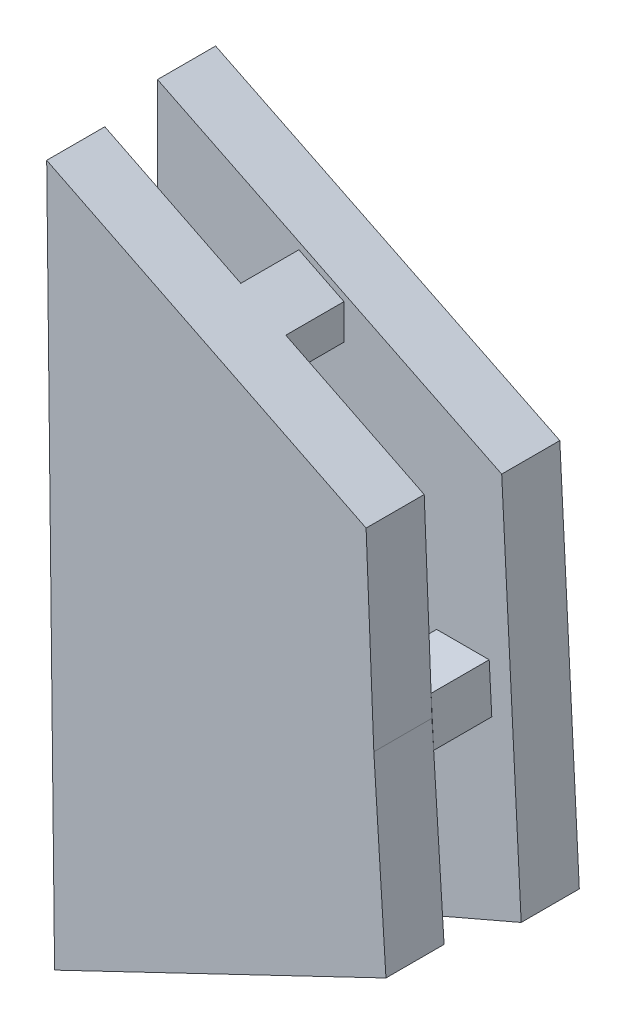
SolidWorks part; units mm, degrees
ref_plane "Front Plane" through (0, 0, 0) normal (0, 0, 1) x (1, 0, 0)
ref_plane "Top Plane" through (0, 0, 0) normal (0, 1, 0) x (1, 0, 0)
ref_plane "Right Plane" through (0, 0, 0) normal (1, 0, 0) x (0, 0, -1)
sketch "Sketch1" plane through (0, 0, 0) normal (0, 1, 0) x (1, 0, 0)
  line L0 (-4.6256, 12.4082) -> (9.4591, -14.08)
  line L1 (9.4591, -14.08) -> (-0.7045, -10.0781)
  line L2 (-0.7045, -10.0781) -> (-8.0443, 3.7254)
  line L3 (-8.0443, 3.7254) -> (-4.6256, 12.4082)
  dimension "D1" = 30
  dimension "D2" = 15.6337
sketch "Sketch20" plane through (0, 0, 0) normal (0, 0, 1) x (1, 0, 0)
  line L0 (-2.79, 109.4322) -> (-1.4345, -10.5678)
  line L2 (53.5013, 49.4322) -> (52.1695, 82.1069)
  line L3 (53.5013, 49.4322) -> (55.5864, 16.7673)
  line L4 (52.1695, 82.1069) -> (-2.79, 109.4322)
  line L5 (-1.4345, -10.5678) -> (55.5864, 16.7673)
  dimension "D1" = 120
extrude "Boss-Extrude1" add sketch "Sketch20" along normal blind 10
sketch "Sketch21" plane through (0, 0, 0) normal (0, 0, -1) x (-1, 0, 0)
  line L0 (2.1534, 53.0757) -> (-6.504, 53.0757)
  line L1 (2.79, 109.4322) -> (1.4345, -10.5678) construction
  line L2 (-6.504, 53.0757) -> (-6.504, 44.7938)
  line L3 (-6.504, 44.7938) -> (2.0599, 44.7938)
  line L4 (2.0599, 44.7938) -> (2.1534, 53.0757)
  line L5 (-53.3528, 53.0757) -> (-44.3058, 53.0757)
  line L6 (-53.5013, 49.4322) -> (-52.1695, 82.1069) construction
  line L7 (-44.3058, 53.0757) -> (-44.3058, 44.7938)
  line L8 (-44.3058, 44.7938) -> (-53.7974, 44.7938)
  line L9 (-55.5864, 16.7673) -> (-53.5013, 49.4322) construction
  line L10 (-53.7974, 44.7938) -> (-53.3528, 53.0757)
  line L11 (-20.6099, 0) -> (-20.6099, 9.1834)
  line L12 (1.4345, -10.5678) -> (-55.5864, 16.7673) construction
  line L13 (-20.6099, 9.1834) -> (-28.3581, 10.9397)
  line L14 (-28.3581, 10.9397) -> (-28.3581, 3.7144)
  line L15 (-28.3581, 3.7144) -> (-20.6099, 0)
  line L16 (-28.3581, 93.9457) -> (-28.3581, 87.9037)
  line L17 (-52.1695, 82.1069) -> (2.79, 109.4322) construction
  line L18 (-28.3581, 87.9037) -> (-20.6099, 87.9037)
  line L19 (-20.6099, 87.9037) -> (-20.6099, 97.798)
  line L20 (-20.6099, 97.798) -> (-28.3581, 93.9457)
extrude "Boss-Extrude2" add sketch "Sketch21" along normal blind 10
sketch "Sketch22" plane through (0, 0, -10) normal (0, 0, -1) x (-1, 0, 0)
  line L0 (-24.484, 1.8572) -> (2.7072, -11.1779)
  line L1 (-28.3581, 3.7144) -> (-20.6099, 0) construction
  line L2 (2.7072, -11.1779) -> (3.7253, 78.9483)
  line L3 (3.7253, 78.9483) -> (3.7253, 110.9971)
  line L4 (3.7253, 110.9971) -> (-55.5024, 81.8143)
  line L5 (-55.5024, 81.8143) -> (-58.8563, 16.6772)
  line L6 (-58.8563, 16.6772) -> (-24.484, 1.8572)
extrude "Boss-Extrude3" add sketch "Sketch22" along normal blind 10
sketch "Bend-Lines1" [suppressed] plane through (0, 0, 0) normal (0, 1, 0) x (1, 0, 0)
sketch "Bounding-Box1" [suppressed] plane through (0, 0, 0) normal (0, 1, 0) x (1, 0, 0)
